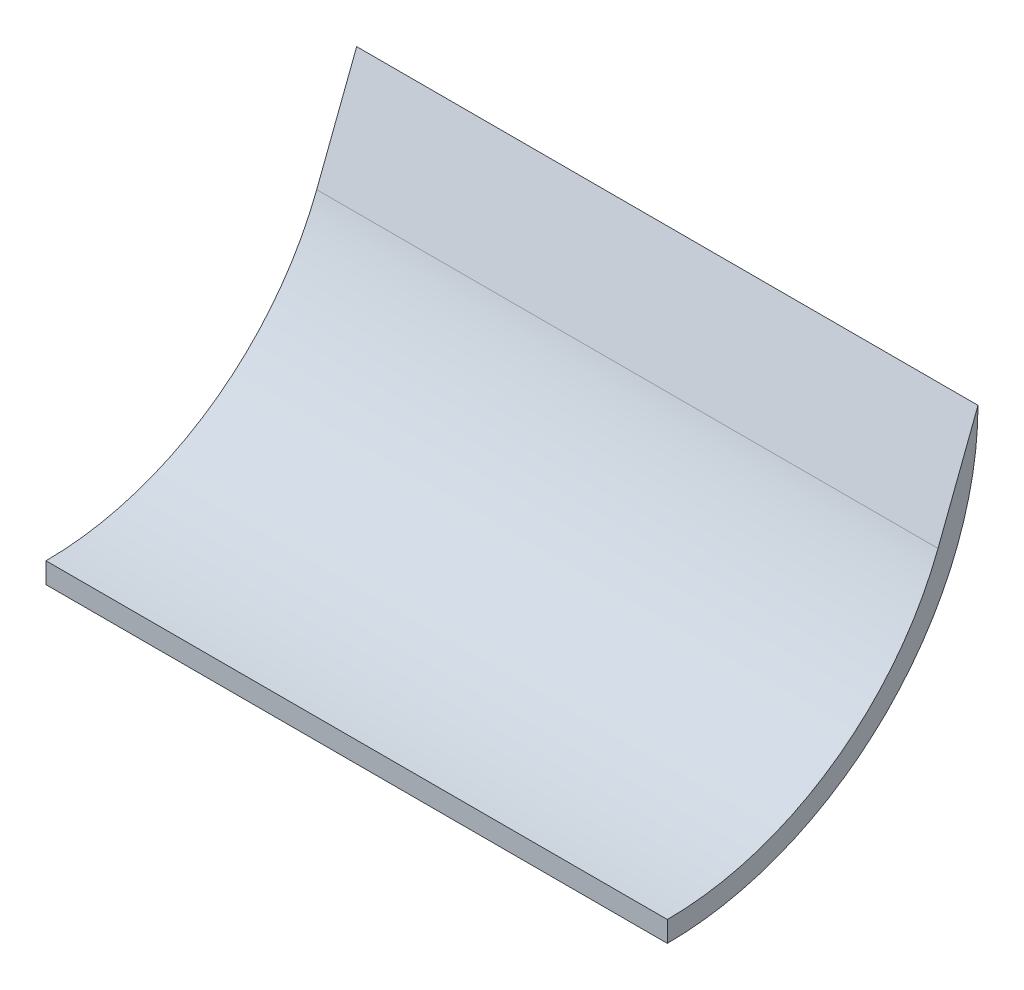
SolidWorks part; units mm, degrees
ref_plane "Plano frontal" through (0, 0, 0) normal (0, 0, 1) x (1, 0, 0)
ref_plane "Plano superior" through (0, 0, 0) normal (0, 1, 0) x (1, 0, 0)
ref_plane "Plano direito" through (0, 0, 0) normal (1, 0, 0) x (0, 0, -1)
sketch "Esboço2" plane through (0, 0, 0) normal (1, 0, 0) x (0, 0, -1)
  line L0 (0, 0) -> (-45, 0) construction
  line L1 (-45, 0) -> (-45, 45) construction
  line L2 (-45, 45) -> (0, 0) construction
  circle A0 centre (-45, 45) radius 45
  dimension "D1" = 45
  dimension "D2" = 45
extrude "Ressalto-extrusão3" add sketch "Esboço2" along normal mid plane 90
sketch "Esboço5" plane through (0, 0, 0) normal (1, 0, 0) x (0, 0, -1)
  circle A0 centre (-45, 45) radius 42
  circle A1 centre (-45, 45) radius 45 construction
  dimension "D1" = 3
extrude "Corte-extrusão1" cut sketch "Esboço5" against normal through all both and the other way through all
sketch "Esboço6" plane through (0, 0, 0) normal (1, 0, 0) x (0, 0, -1)
  line L0 (-45, 45) -> (-45, 0)
  line L1 (-45, 0) -> (-90, 0)
  line L2 (-90, 0) -> (-90, 45)
  line L3 (-90, 45) -> (-90, 90)
  line L4 (-90, 90) -> (-45, 90)
  line L5 (-45, 90) -> (-3, 90)
  line L6 (-3, 90) -> (0, 90)
  line L7 (0, 45) -> (-5.8107, 29.8937)
  line L8 (-5.8107, 29.8937) -> (-45, 45)
  line L9 (0, 45) -> (0, 90)
  circle A0 centre (-45, 45) radius 45 construction
  circle A2 centre (-45, 45) radius 42 construction
extrude "Corte-extrusão2" cut sketch "Esboço6" against normal through all both and the other way through all
